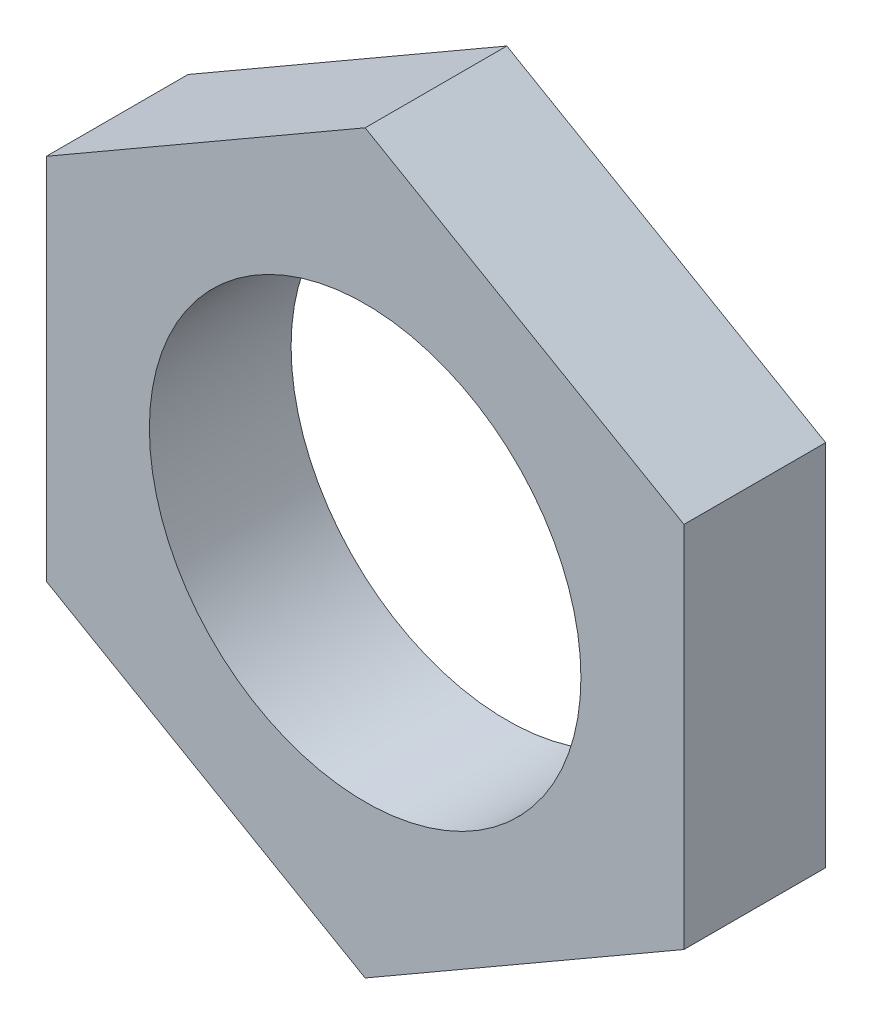
SolidWorks part; units mm, degrees
ref_plane "前视基准面" through (0, 0, 0) normal (0, 0, 1) x (1, 0, 0)
ref_plane "上视基准面" through (0, 0, 0) normal (0, 1, 0) x (1, 0, 0)
ref_plane "右视基准面" through (0, 0, 0) normal (1, 0, 0) x (0, 0, -1)
sketch "草图1" plane through (0, 0, 0) normal (0, 0, 1) x (1, 0, 0)
  line L1 (0, 5.7158) -> (-4.95, 2.8579)
  line L2 (-4.95, 2.8579) -> (-4.95, -2.8579)
  line L3 (-4.95, -2.8579) -> (0, -5.7158)
  line L4 (0, -5.7158) -> (4.95, -2.8579)
  line L5 (4.95, -2.8579) -> (4.95, 2.8579)
  line L6 (4.95, 2.8579) -> (0, 5.7158)
  circle A0 centre (0, 0) radius 4.95 construction
  circle A1 centre (0, 0) radius 3.35
  dimension "D2" = 6.7
  dimension "D1" = 9.9
extrude "凸台-拉伸1" add sketch "草图1" along normal blind 2.2
cosmetic thread "装饰螺纹线1" parameters "D2"=10
